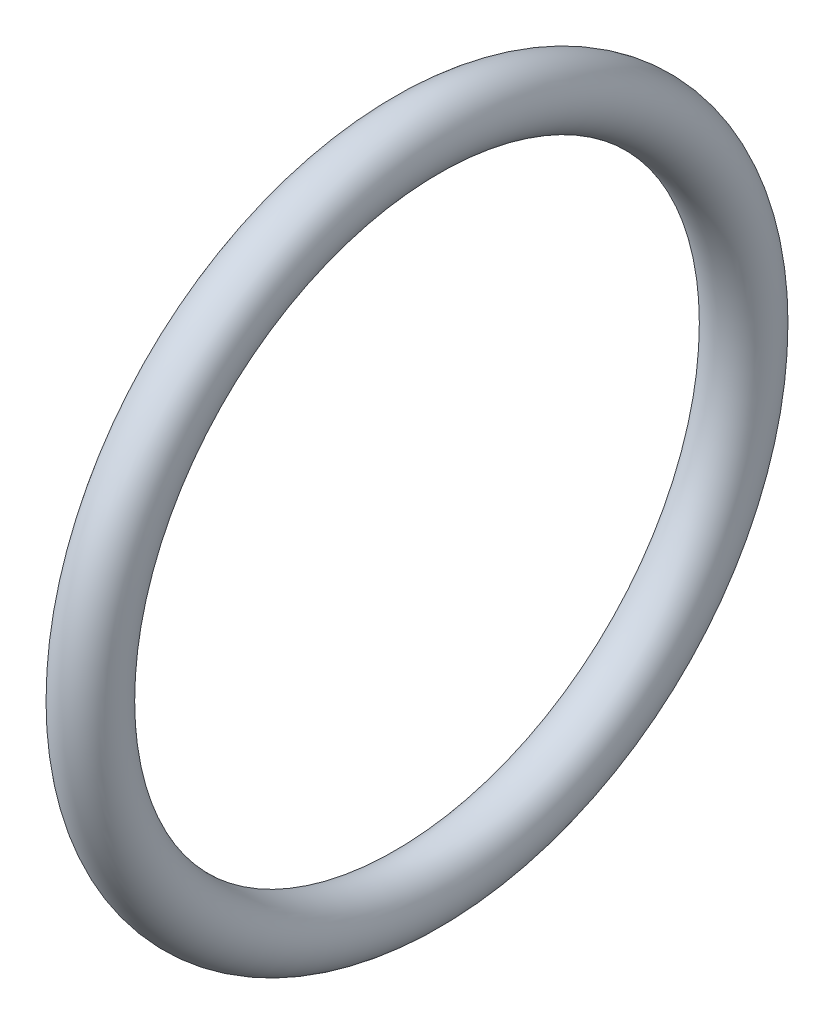
SolidWorks part; units mm, degrees
material "Резина"
ref_plane "Front Plane" through (0, 0, 0) normal (0, 0, 1) x (1, 0, 0)
ref_plane "Top Plane" through (0, 0, 0) normal (0, 1, 0) x (1, 0, 0)
ref_plane "Right Plane" through (0, 0, 0) normal (1, 0, 0) x (0, 0, -1)
sketch "Sketch1" plane through (0, 0, 0) normal (0, 0, 1) x (1, 0, 0)
  line L0 (-8.9776, 0) -> (8.9776, 0) construction
  line L8 (-5, 35) -> (-32.4833, 35)
  line L9 (-32.4833, 35) -> (-32.4833, 20)
  line L10 (-32.4833, 20) -> (17.5167, 20)
  line L11 (17.5167, 20) -> (17.5167, 22)
  line L12 (17.5167, 22) -> (10.4317, 26.0905)
  line L13 (10.4317, 26.0905) -> (9.6817, 24.7915)
  line L14 (5.3516, 27.2915) -> (6.1016, 28.5905)
  line L15 (6.1016, 28.5905) -> (-5, 35)
  arc A1 (5.3516, 27.2915) -> (9.6817, 24.7915) centre (7.5167, 26.0415) ccw
  circle A2 centre (7.5167, 26.0415) radius 2.5
  dimension "D1" = 0
revolve "Revolve1" add sketch "Sketch1" angle 360 about L0
